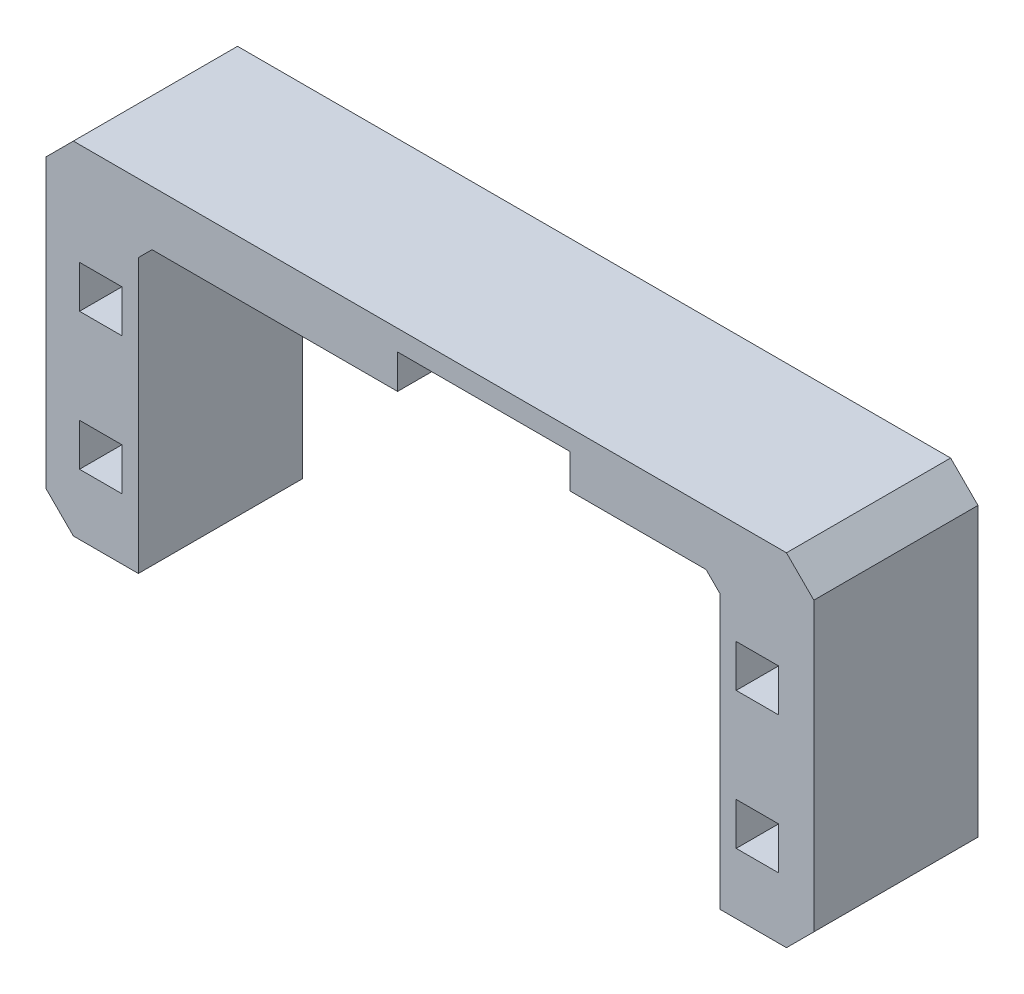
SolidWorks part; units mm, degrees
ref_plane "Plano frontal" through (0, 0, 0) normal (0, 0, 1) x (1, 0, 0)
ref_plane "Plano superior" through (0, 0, 0) normal (0, 1, 0) x (1, 0, 0)
ref_plane "Plano direito" through (0, 0, 0) normal (1, 0, 0) x (0, 0, -1)
sketch "Esboço2" plane through (0, 0, 0) normal (0, 0, 1) x (1, 0, 0)
  line L0 (24.23, 36.1287) -> (26.73, 36.1287)
  line L1 (26.73, 36.1287) -> (26.73, 33.6287)
  line L2 (26.73, 33.6287) -> (24.23, 33.6287)
  line L3 (24.23, 33.6287) -> (24.23, 36.1287)
  line L4 (24.23, 26.1287) -> (26.73, 26.1287)
  line L5 (26.73, 26.1287) -> (26.73, 23.6287)
  line L6 (26.73, 23.6287) -> (24.23, 23.6287)
  line L7 (24.23, 23.6287) -> (24.23, 26.1287)
  line L8 (72.23, 33.6287) -> (72.23, 36.1287)
  line L9 (70.73, 18.8787) -> (75.605, 18.8787)
  line L10 (77.605, 20.8787) -> (77.605, 41.8787)
  line L11 (72.23, 36.1287) -> (74.73, 36.1287)
  line L12 (74.73, 36.1287) -> (74.73, 33.6287)
  line L13 (74.73, 33.6287) -> (72.23, 33.6287)
  line L14 (72.23, 26.1287) -> (74.73, 26.1287)
  line L15 (74.73, 26.1287) -> (74.73, 23.6287)
  line L16 (74.73, 23.6287) -> (72.23, 23.6287)
  line L17 (72.23, 23.6287) -> (72.23, 26.1287)
  line L18 (24.23, 33.6287) -> (26.73, 36.1287) construction
  line L19 (24.23, 23.6287) -> (26.73, 26.1287) construction
  line L20 (72.23, 33.6287) -> (74.73, 36.1287) construction
  line L21 (72.23, 23.6287) -> (74.73, 26.1287) construction
  line L22 (23.48, 18.8787) -> (28.23, 18.8787)
  line L23 (21.48, 41.8787) -> (23.48, 43.8787)
  line L24 (29.23, 39.8787) -> (46.48, 39.8787)
  line L25 (53.48, 42.3787) -> (60.48, 42.3787)
  line L26 (53.48, 42.3787) -> (46.48, 42.3787)
  line L27 (73.48, 24.8787) -> (72.23, 24.8787) construction
  line L28 (23.48, 43.8787) -> (75.605, 43.8787)
  line L29 (77.605, 41.8787) -> (75.605, 43.8787)
  line L30 (75.605, 18.8787) -> (77.605, 20.8787)
  line L31 (23.48, 18.8787) -> (21.48, 20.8787)
  line L32 (28.23, 38.8787) -> (29.23, 39.8787)
  line L33 (21.48, 20.8787) -> (21.48, 41.8787)
  line L34 (25.48, 34.8787) -> (25.48, 24.8787) construction
  line L35 (25.48, 24.8787) -> (25.48, 29.8787) construction
  line L36 (25.48, 23.6287) -> (25.48, 18.8787) construction
  line L37 (73.48, 34.8787) -> (73.48, 24.8787) construction
  line L38 (73.48, 24.8787) -> (73.48, 29.8787) construction
  line L39 (73.48, 29.8787) -> (25.48, 29.8787) construction
  line L40 (25.48, 18.8787) -> (21.48, 18.8787) construction
  line L41 (70.73, 38.8787) -> (69.73, 39.8787)
  line L42 (28.23, 18.8787) -> (28.23, 38.8787)
  line L43 (60.48, 42.3787) -> (60.48, 39.8787)
  line L45 (53.48, 43.8787) -> (53.48, 42.3787) construction
  line L46 (46.48, 42.3787) -> (46.48, 39.8787)
  line L47 (72.23, 24.8787) -> (70.73, 24.8787) construction
  line L48 (70.73, 24.8787) -> (70.73, 18.8787) construction
  line L49 (70.73, 18.8787) -> (70.73, 38.8787)
  line L50 (69.73, 39.8787) -> (60.48, 39.8787)
  point P3 (77.605, 18.8787)
  point P8 (77.605, 43.8787)
  point P36 (21.48, 43.8787)
  point P66 (28.23, 39.8787)
  point P70 (53.48, 43.8787)
  point P73 (70.73, 39.8787)
extrude "Ressalto-extrusão1" add sketch "Esboço2" along normal blind 12
sketch "Esboço5" plane through (0, 0, 0) normal (0, 0, -1) x (-1, 0, 0)
  line L0 (-60.48, 39.8787) -> (-59.78, 39.8787)
  line L1 (-59.78, 39.8787) -> (-59.78, 42.3787)
  line L2 (-46.48, 42.3787) -> (-60.48, 42.3787) construction
  line L3 (-59.78, 42.3787) -> (-60.48, 42.3787)
  line L4 (-60.48, 42.3787) -> (-60.48, 39.8787) construction
  line L5 (-60.48, 42.3787) -> (-60.48, 39.8787)
  line L6 (-46.48, 39.8787) -> (-47.18, 39.8787)
  line L7 (-47.18, 39.8787) -> (-47.18, 42.3787)
  line L8 (-47.18, 42.3787) -> (-46.48, 42.3787)
  line L9 (-46.48, 42.3787) -> (-46.48, 39.8787)
  dimension "D1" = 0.7
  dimension "D2" = 0.7
extrude "Ressalto-extrusão2" add sketch "Esboço5" against normal through all
sketch "Esboço7" plane through (0, 0, 0) normal (0, 0, -1) x (-1, 0, 0)
  line L0 (-74.73, 34.8787) -> (-72.23, 34.8787) construction
  line L1 (-74.73, 33.6287) -> (-74.73, 36.1287) construction
  line L2 (-72.23, 36.1287) -> (-72.23, 33.6287) construction
  line L3 (-27.03, 26.4287) -> (-23.93, 23.3287) construction
  line L4 (-74.73, 23.6287) -> (-74.73, 26.1287) construction
  line L5 (-74.73, 24.8787) -> (-72.23, 24.8787) construction
  line L6 (-72.23, 26.1287) -> (-72.23, 23.6287) construction
  line L7 (-75.03, 36.4287) -> (-71.93, 36.4287)
  line L8 (-26.73, 23.6287) -> (-26.73, 26.1287) construction
  line L9 (-26.73, 24.8787) -> (-24.23, 24.8787) construction
  line L10 (-24.23, 26.1287) -> (-24.23, 23.6287) construction
  line L11 (-75.03, 36.4287) -> (-75.03, 33.3287)
  line L12 (-24.23, 36.1287) -> (-24.23, 33.6287) construction
  line L13 (-24.23, 34.8787) -> (-26.73, 34.8787) construction
  line L14 (-26.73, 33.6287) -> (-26.73, 36.1287) construction
  line L15 (-75.03, 33.3287) -> (-71.93, 33.3287)
  line L16 (-71.93, 36.4287) -> (-71.93, 33.3287)
  line L17 (-75.03, 36.4287) -> (-71.93, 33.3287) construction
  line L18 (-75.03, 33.3287) -> (-71.93, 36.4287) construction
  line L19 (-75.03, 26.4287) -> (-71.93, 26.4287)
  line L20 (-75.03, 26.4287) -> (-75.03, 23.3287)
  line L21 (-75.03, 23.3287) -> (-71.93, 23.3287)
  line L22 (-71.93, 26.4287) -> (-71.93, 23.3287)
  line L23 (-75.03, 26.4287) -> (-71.93, 23.3287) construction
  line L24 (-75.03, 23.3287) -> (-71.93, 26.4287) construction
  line L25 (-27.03, 26.4287) -> (-27.03, 23.3287)
  line L26 (-23.93, 26.4287) -> (-23.93, 23.3287)
  line L27 (-27.03, 23.3287) -> (-23.93, 26.4287) construction
  line L28 (-27.03, 26.4287) -> (-23.93, 26.4287)
  line L29 (-27.03, 23.3287) -> (-23.93, 23.3287)
  line L30 (-27.03, 36.4287) -> (-23.93, 33.3287) construction
  line L31 (-27.03, 36.4287) -> (-27.03, 33.3287)
  line L32 (-23.93, 36.4287) -> (-23.93, 33.3287)
  line L33 (-27.03, 33.3287) -> (-23.93, 36.4287) construction
  line L34 (-27.03, 36.4287) -> (-23.93, 36.4287)
  line L35 (-27.03, 33.3287) -> (-23.93, 33.3287)
  point P12 (-73.48, 34.8787)
  point P29 (-73.48, 24.8787)
  point P34 (-25.48, 24.8787)
  point P39 (-25.48, 34.8787)
extrude "Corte-extrusão5" cut sketch "Esboço7" against normal through all
